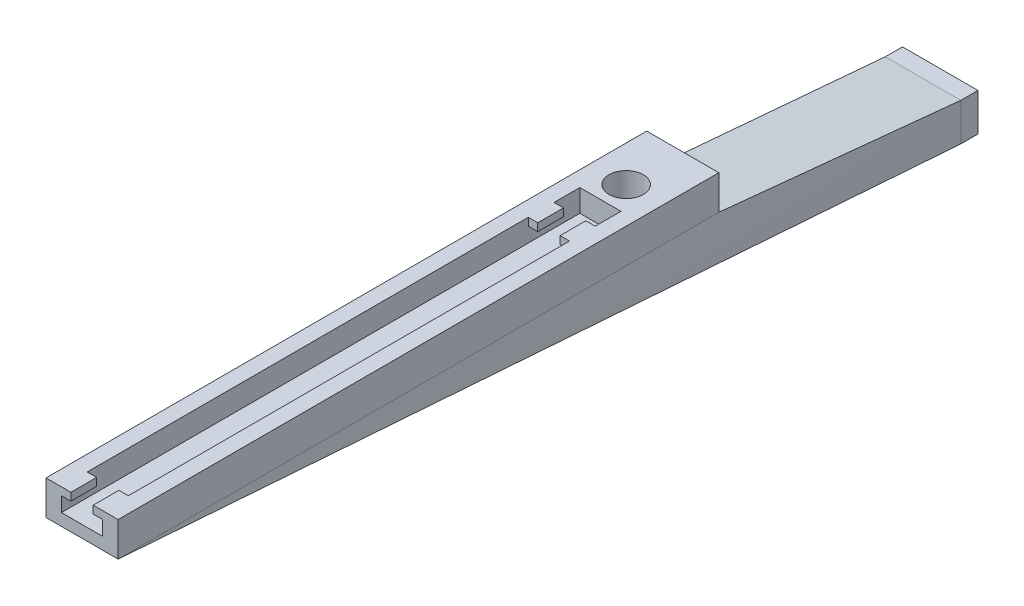
SolidWorks part; units mm, degrees
ref_plane "Front Plane" through (0, 0, 0) normal (1, 0, 0) x (0, 1, 0)
ref_plane "Top Plane" through (0, 0, 0) normal (0, 0, 1) x (0, 1, 0)
ref_plane "Right Plane" through (0, 0, 0) normal (0, 1, 0) x (-1, 0, 0)
sketch "Sketch1" plane through (0, 0, 0) normal (0, 0, 1) x (0, 1, 0)
  line L1 (-5.5, -11) -> (5.5, -11)
  line L2 (-5.5, -11) -> (-5.5, 11)
  line L3 (-5.5, 11) -> (5.5, 11)
  line L4 (5.5, -11) -> (5.5, 11)
  line L5 (-5.5, -11) -> (5.5, 11) construction
  line L6 (-5.5, 11) -> (5.5, -11) construction
  point P0 (0, 0)
  dimension "D1" = 11
  dimension "D2" = 22
extrude "Boss-Extrude1" add sketch "Sketch1" along normal blind 5
ref_plane "Plane2" through (0, 22, 0) normal (0, 1, 0) x (-1, 0, 0)
sketch "Sketch3" plane through (0, 22, 0) normal (0, 1, 0) x (-1, 0, 0)
  line L1 (10.5, 75) -> (-10.5, 75)
  line L2 (10.5, 75) -> (10.5, 250)
  line L3 (10.5, 250) -> (-10.5, 250)
  line L4 (-10.5, 75) -> (-10.5, 250)
  line L5 (10.5, 75) -> (-10.5, 250) construction
  line L6 (10.5, 250) -> (-10.5, 75) construction
  point P0 (0, 162.5)
  dimension "D1" = 175
  dimension "D2" = 21
  dimension "D3" = 250
extrude "Boss-Extrude2" add sketch "Sketch3" against normal blind 10 separate body
loft "Loft1" add section face at (0, 12, 162.5) section face at (0, 0, 5)
sketch "Sketch4" plane through (0, 0, 250) normal (0, 0, 1) x (1, 0, 0)
  line L0 (0, -1000) -> (0, 49000) construction
  line L1 (-1006.0953, 22) -> (48993.9047, 22) construction
  line L3 (-3.25, 22) -> (-3.25, 19.75)
  line L4 (-3.25, 19.75) -> (-6, 19.75)
  line L5 (-6, 19.75) -> (-6, 15.5)
  line L6 (-6, 15.5) -> (6, 15.5)
  line L7 (-3.25, 22) -> (3.25, 22)
  line L8 (12.1, 22) -> (-12.1, 22) construction
  line L9 (6, 19.75) -> (6, 15.5)
  line L10 (3.25, 19.75) -> (6, 19.75)
  line L11 (3.25, 22) -> (3.25, 19.75)
  point P14 (0, 22)
  point P15 (0, 15.5)
  dimension "D1" = 6
  dimension "D2" = 6.5
  dimension "D3" = 3.25
  dimension "D4" = 2.25
extrude "Cut-Extrude1" cut sketch "Sketch4" against normal blind 151
sketch "Sketch5" plane through (0, 22, 0) normal (0, 1, 0) x (-1, 0, 0)
  line L1 (6, 99) -> (-6, 99) construction
  circle A0 centre (0, 91.5) radius 5
  dimension "D1" = 10
  dimension "D2" = 7.5
extrude "Cut-Extrude2" cut sketch "Sketch5" against normal blind 15
sketch "Sketch6" plane through (0, 22, 0) normal (0, 1, 0) x (-1, 0, 0)
  line L0 (0, -1000) -> (0, 49000) construction
  line L2 (6, 242.5) -> (6, 114)
  line L3 (6, 114) -> (-6, 114)
  line L5 (6, 99) -> (-6, 99) construction
  line L6 (-6, 106.5) -> (6, 106.5)
  line L7 (6, 106.5) -> (6, 99)
  line L8 (6, 99) -> (-6, 99)
  line L9 (-3.25, 99) -> (3.25, 99) construction
  line L10 (-6, 106.5) -> (-6, 99)
  line L11 (-6, 242.5) -> (-6, 114)
  line L12 (-6, 242.5) -> (6, 242.5)
  line L13 (6, 250) -> (-6, 250) construction
  point P18 (0, 99)
  point P19 (0, 106.5)
  point P20 (0, 114)
  point P21 (0, 250)
  dimension "D1" = 6
  dimension "D2" = 7.5
  dimension "D3" = 15
  dimension "D4" = 6
  dimension "D5" = 7.5
extrude "Cut-Extrude3" cut sketch "Sketch6" against normal up to next
